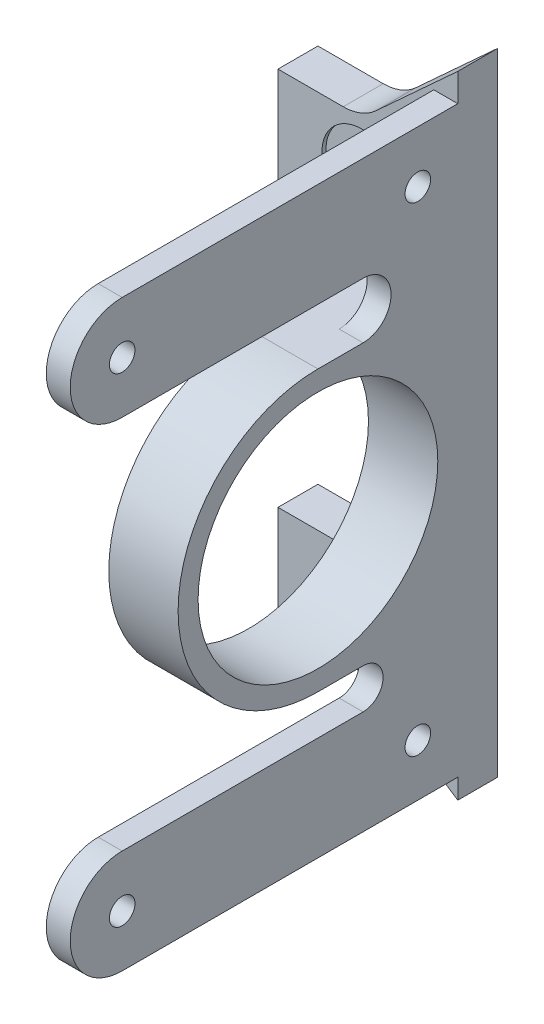
SolidWorks part; units mm, degrees
ref_plane "前视基准面" through (0, 0, 0) normal (0, 0, 1) x (1, 0, 0)
ref_plane "上视基准面" through (0, 0, 0) normal (0, 1, 0) x (1, 0, 0)
ref_plane "右视基准面" through (0, 0, 0) normal (1, 0, 0) x (0, 0, -1)
sketch "草图2" plane through (0, 0, 0) normal (0, 0, 1) x (1, 0, 0)
  line L0 (-14.7736, 24.3382) -> (-14.7736, -35.6618)
  line L1 (-14.7736, -35.6618) -> (30.2264, -35.6618)
  line L2 (7.7264, -35.6618) -> (7.7264, -23.1618)
  line L3 (21.55, -23.1618) -> (-6.0971, -23.1618)
  line L4 (-6.0971, -23.1618) -> (-6.0971, 11.8382)
  line L5 (-6.0971, 11.8382) -> (21.55, 11.8382)
  line L6 (7.7264, 11.8382) -> (7.7264, 24.3382)
  line L7 (30.2264, 24.3382) -> (-14.7736, 24.3382)
  line L8 (7.7264, 28.8603) -> (7.7264, -39.8897) construction
  line L9 (21.55, -23.1618) -> (21.55, 11.8382)
  line L10 (30.2264, 24.3382) -> (30.2264, -35.6618)
  line L11 (-18.1559, -5.6618) -> (33.2411, -5.6618) construction
  point P16 (-6.0971, -5.6618)
  point P17 (-14.7736, -5.6618)
  dimension "D1" = 45
  dimension "D2" = 35
  dimension "D3" = 60
extrude "凸台-拉伸2" add sketch "草图2" along normal blind 5 contours L6 L7 L0 L1 L2 L3 L4 L5 | L10 L7 L6 L5 L9 L3 L2 L1
sketch "草图4" plane through (0, 0, 5) normal (0, 0, 1) x (1, 0, 0)
  line L0 (-18.165, -5.6618) -> (33.9165, -5.6618) construction
  line L1 (-14.7736, 24.3382) -> (-14.7736, -35.6618) construction
  line L2 (-14.7736, -23.1618) -> (-6.0971, -23.1618)
  line L3 (-14.7736, -23.1618) -> (-14.7736, 11.8382)
  line L4 (-14.7736, 11.8382) -> (-6.0971, 11.8382)
  line L5 (-6.0971, -23.1618) -> (-6.0971, 11.8382)
  line L6 (-6.0971, -23.1618) -> (-6.0971, 11.8382) construction
  line L7 (7.7264, -39.813) -> (7.7264, 28.1228) construction
  line L8 (30.2264, 11.8382) -> (21.55, 11.8382)
  line L9 (21.55, -23.1618) -> (21.55, 11.8382)
  line L10 (30.2264, -23.1618) -> (21.55, -23.1618)
  line L11 (30.2264, -23.1618) -> (30.2264, 11.8382)
  point P17 (-14.7736, -5.6618)
  dimension "D1" = 35
extrude "凸台-拉伸15" add sketch "草图4" along normal blind 35
sketch "草图5" plane through (-14.7736, 0, 0) normal (-1, 0, 0) x (0, 0, 1)
  line L0 (0, -5.6618) -> (40, -5.6618)
  line L1 (0, 24.3382) -> (0, -35.6618) construction
  line L2 (40, 11.8382) -> (40, -23.1618) construction
  line L3 (22.5, 11.8382) -> (40, 11.8382)
  line L4 (40, 11.8382) -> (40, -23.1618)
  line L5 (40, -23.1618) -> (22.5, -23.1618)
  circle A0 centre (22.5, -5.6618) radius 17.5
  line M5 (5, -23.1618) -> (40, -23.1618)
  line M6 (40, -23.1618) -> (40, 11.8382)
  line M7 (40, 11.8382) -> (5, 11.8382)
  dimension "D1" = 35
extrude "切除-拉伸1" cut sketch "草图5" against normal blind 45 contours A0 M5 M6 | A0 M6 M7
sketch "草图6" plane through (-14.7736, 0, 0) normal (-1, 0, 0) x (0, 0, 1)
  circle A0 centre (22.5, -5.6618) radius 15
extrude "切除-拉伸2" cut sketch "草图6" against normal blind 45
fillet "圆角1" radius 5 4 edges at (-6.0971, 11.8382, 2.5) (21.55, 11.8382, 2.5) (-6.0971, -23.1618, 2.5) (21.55, -23.1618, 2.5)
sketch "草图7" plane through (-6.0971, 0, 0) normal (1, 0, 0) x (0, 0, -1)
  circle A0 centre (-22.5, -5.6618) radius 15
  circle A1 centre (-22.5, -5.6618) radius 13
extrude "凸台-拉伸16" add sketch "草图7" against normal blind 1
sketch "草图8" plane through (21.55, 0, 0) normal (-1, 0, 0) x (0, 0, 1)
  circle A0 centre (22.5, -5.6618) radius 15
  circle A1 centre (22.5, -5.6618) radius 10
sketch "草图9" plane through (0, 0, 5) normal (0, 0, 1) x (1, 0, 0)
  line L0 (7.7264, 24.3382) -> (7.7264, -35.6618)
  line L13 (30.2264, 24.3382) -> (-14.7736, 24.3382) construction
  line L14 (-14.7736, -35.6618) -> (30.2264, -35.6618) construction
sketch "草图11" plane through (0, 0, 5) normal (0, 0, 1) x (1, 0, 0)
  line L0 (-14.7736, 18.0882) -> (30.2264, 18.0882)
  line L1 (-14.7736, 24.3382) -> (-14.7736, 11.8382) construction
  line L2 (30.2264, 24.3382) -> (30.2264, 11.8382) construction
  line L3 (7.7264, 24.3382) -> (7.7264, -35.6618) construction
  line L4 (30.2264, 24.3382) -> (-14.7736, 24.3382) construction
  line L5 (-14.7736, -35.6618) -> (30.2264, -35.6618) construction
  line L6 (7.7264, -5.6618) -> (45.6912, -5.6618) construction
  line L7 (45.6912, -5.6618) -> (45.6912, 4.9969) construction
  line L10 (-14.7736, -29.4118) -> (30.2264, -29.4118)
  line L11 (-14.7736, -23.1618) -> (-14.7736, -35.6618) construction
  point P4 (-2.7736, 18.0882)
  point P16 (-2.7736, -29.4118)
  point P18 (18.2264, -29.4118)
  point P25 (18.2264, 18.0882)
  dimension "D1" = 12
split "分割1" trim tools "草图9" bodies to split 111 resulting bodies 117 118
delete or keep bodies "实体-删除/保留 2" type delete bodies bodies 117
sketch "草图17" plane through (0, 0, 5) normal (0, 0, 1) x (1, 0, 0)
  line L0 (30.2264, -23.1618) -> (30.2264, -35.6618) construction
  line L1 (30.2264, -41.1618) -> (27.2264, -41.1618)
  line L2 (30.2264, -41.1618) -> (30.2264, -28.1618)
  line L3 (30.2264, -28.1618) -> (27.2264, -28.1618)
  line L4 (27.2264, -41.1618) -> (27.2264, -28.1618)
  line L5 (30.2264, 31.8382) -> (27.2264, 31.8382)
  line L6 (30.2264, 31.8382) -> (30.2264, 18.8382)
  line L7 (30.2264, 18.8382) -> (27.2264, 18.8382)
  line L8 (27.2264, 31.8382) -> (27.2264, 18.8382)
  line L9 (21.55, -23.1618) -> (30.2264, -23.1618) construction
  line L10 (30.2264, 24.3382) -> (30.2264, 11.8382) construction
  line L11 (30.2264, 11.8382) -> (21.55, 11.8382) construction
  point P4 (0, 0)
  dimension "D1" = 3
  dimension "D2" = 3
  dimension "D3" = 13
  dimension "D4" = 13
  dimension "D5" = 7
  dimension "D6" = 5
extrude "凸台-拉伸20" add sketch "草图17" along normal blind 42
hole_wizard "打孔尺寸(%根据六角头螺)栓 全螺纹的类型1" positions "3D草图2" profile "草图31" counterbore size "M4" standard "GB"
sketch3d "3D草图2"
  point P0 (18.2264, 18.0882, 5)
  point P3 (18.2264, -29.4118, 5)
sketch "草图31" plane through (18.2264, 18.0882, 5) normal (1, 0, 0) x (0, -1, 0)
  line L0 (0, 0) -> (0, 6.2919)
  line L1 (0, 6.2919) -> (2.15, 5)
  line L2 (2.15, 5) -> (2.15, 0.5)
  line L3 (2.15, 0.5) -> (5, 0.5)
  line L4 (5, 0.5) -> (5, 0)
  line L5 (5, 0) -> (0, 0)
  line L10 (0, 6.2919) -> (-2.15, 5) construction
  line L11 (0, -6.35) -> (0, 107.95) construction
  dimension "孔直径" = 4.3
  dimension "孔深度" = 5
  dimension "柱形沉头孔直径" = 10
  dimension "柱形沉头孔深度" = 0.5
  dimension "导头角度" = 118
sketch "草图32" plane through (30.2264, 0, 0) normal (1, 0, 0) x (0, 0, -1)
  line L0 (-47, 18.8382) -> (-47, 31.8382) construction
  line L1 (-47, -41.1618) -> (-47, -28.1618) construction
  line L2 (-47, 31.8382) -> (-47, 18.8382)
  line L3 (-47, -28.1618) -> (-47, -41.1618)
  line L4 (-22.5, 11.8382) -> (-5, 11.8382) construction
  line L5 (-47, 18.8382) -> (-5, 18.8382) construction
  line L6 (-16.8515, 11.8382) -> (-5, 11.8382)
  line L7 (-5, 11.8382) -> (-5, 18.8382)
  line L8 (-5, 18.8382) -> (-16.8515, 18.8382)
  line L9 (-47, -28.1618) -> (-5, -28.1618) construction
  line L10 (-22.5, -23.1618) -> (-5, -23.1618) construction
  line L11 (-16.8515, -23.1618) -> (-5, -23.1618)
  line L12 (-5, -23.1618) -> (-5, -28.1618)
  line L13 (-5, -28.1618) -> (-16.8515, -28.1618)
  arc A0 (-47, 31.8382) -> (-47, 18.8382) centre (-47, 25.3382) ccw
  arc A1 (-47, -28.1618) -> (-47, -41.1618) centre (-47, -34.6618) ccw
  arc A2 (-16.8515, 11.8382) -> (-16.8515, 18.8382) centre (-16.8515, 15.3382) ccw
  arc A3 (-16.8515, -28.1618) -> (-16.8515, -23.1618) centre (-16.8515, -25.6618) ccw
  point P22 (0, 0)
extrude "凸台-拉伸21" add sketch "草图32" against normal blind 3
sketch "草图33" plane through (30.2264, 0, 0) normal (1, 0, 0) x (0, 0, -1)
  circle A0 centre (-47, 25.3382) radius 1.6
  circle A1 centre (-47, -34.6618) radius 1.6
  circle A2 centre (-10, 25.3382) radius 1.6
  circle A3 centre (-10, -34.6618) radius 1.6
  point P10 (0, 0)
  dimension "D1" = 37
  dimension "D2" = 37
extrude "切除-拉伸3" cut sketch "草图33" against normal blind 3
sketch "草图34" plane through (0, 0, 5) normal (0, 0, 1) x (1, 0, 0)
  line L0 (18.2264, 24.3382) -> (30.2264, 24.3382)
  line L1 (27.2264, 24.3382) -> (7.7264, 24.3382) construction
  line L2 (30.2264, 24.3382) -> (30.2264, 35.3382)
  line L3 (30.2264, 35.3382) -> (18.2264, 24.3382)
  line L4 (18.2264, -35.6618) -> (30.2264, -35.6618)
  line L5 (7.7264, -35.6618) -> (27.2264, -35.6618) construction
  line L6 (30.2264, -35.6618) -> (30.2264, -43.6618)
  line L7 (30.2264, -43.6618) -> (18.2264, -35.6618)
  dimension "D1" = 11
  dimension "D2" = 12
  dimension "D3" = 8
extrude "凸台-拉伸22" add sketch "草图34" against normal blind 5
fillet "圆角2" radius 6 2 edges at (18.2264, -35.6618, 2.5) (18.2264, 24.3382, 2.5)
